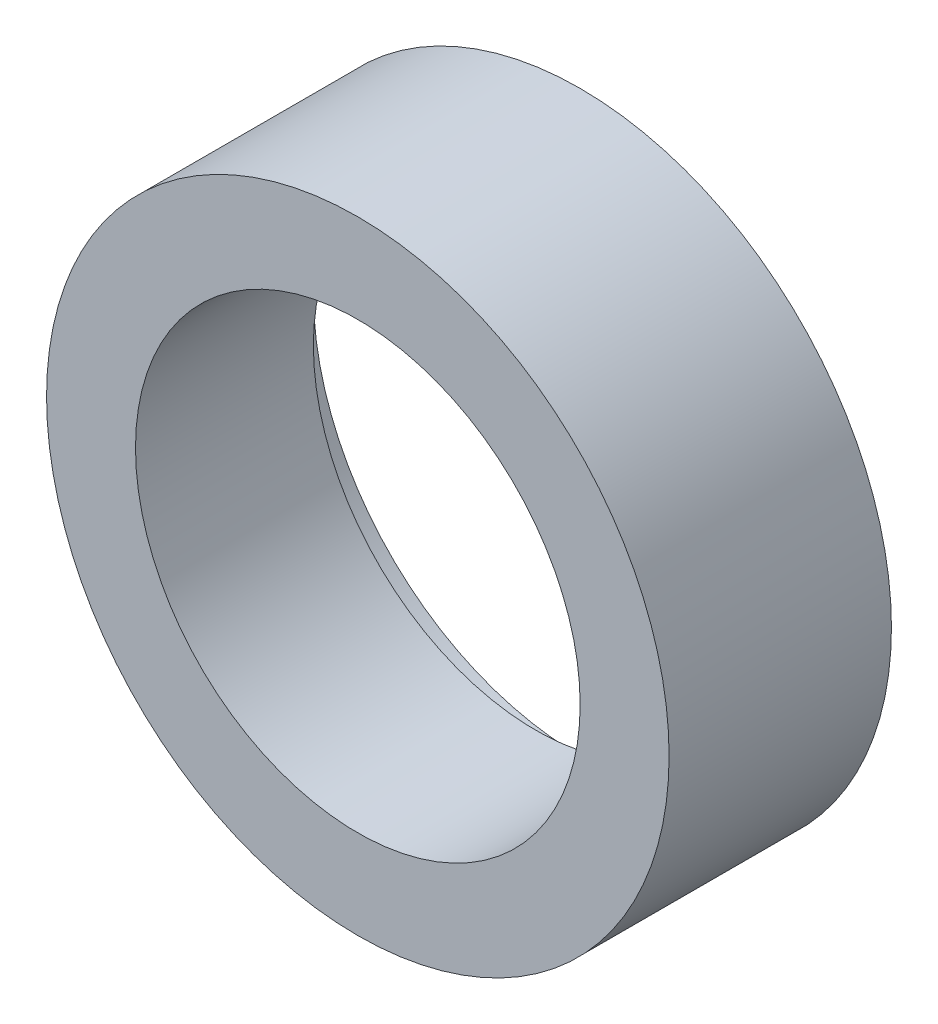
SolidWorks part; units mm, degrees
material "6061-T6 (SS)"
ref_plane "Front Plane" through (0, 0, 0) normal (0, 0, 1) x (1, 0, 0)
ref_plane "Top Plane" through (0, 0, 0) normal (0, 1, 0) x (1, 0, 0)
ref_plane "Right Plane" through (0, 0, 0) normal (1, 0, 0) x (0, 0, -1)
sketch "Sketch1" plane through (0, 0, 0) normal (0, 1, 0) x (1, 0, 0)
  line L0 (0, 0.3483) -> (0, 0.6138) construction
  line L1 (-15.875, -7.9375) -> (15.875, -7.9375) construction
  line L2 (-15.875, -7.9375) -> (-15.875, 7.9375) construction
  line L3 (-15.875, 7.9375) -> (15.875, 7.9375) construction
  line L4 (15.875, -7.9375) -> (15.875, 7.9375) construction
  line L5 (-15.875, -7.9375) -> (15.875, 7.9375) construction
  line L6 (-15.875, 7.9375) -> (15.875, -7.9375) construction
  line L7 (15.875, -7.9375) -> (19.05, -7.9375)
  line L8 (15.875, -7.9375) -> (15.875, 4.7625)
  line L9 (15.875, 4.7625) -> (19.05, 4.7625)
  line L10 (19.05, -7.9375) -> (19.05, 4.7625)
  line L11 (19.05, -7.9375) -> (22.225, -7.9375)
  line L12 (19.05, -7.9375) -> (19.05, 7.9375)
  line L13 (19.05, 7.9375) -> (22.225, 7.9375)
  line L14 (22.225, -7.9375) -> (22.225, 7.9375)
  point P0 (0, 0)
  dimension "D1" = 31.75
  dimension "D2" = 15.875
  dimension "D3" = 22.225
  dimension "D4" = 3.175
  dimension "D5" = 3.175
revolve "Revolve1" add sketch "Sketch1" angle 360 about L0
